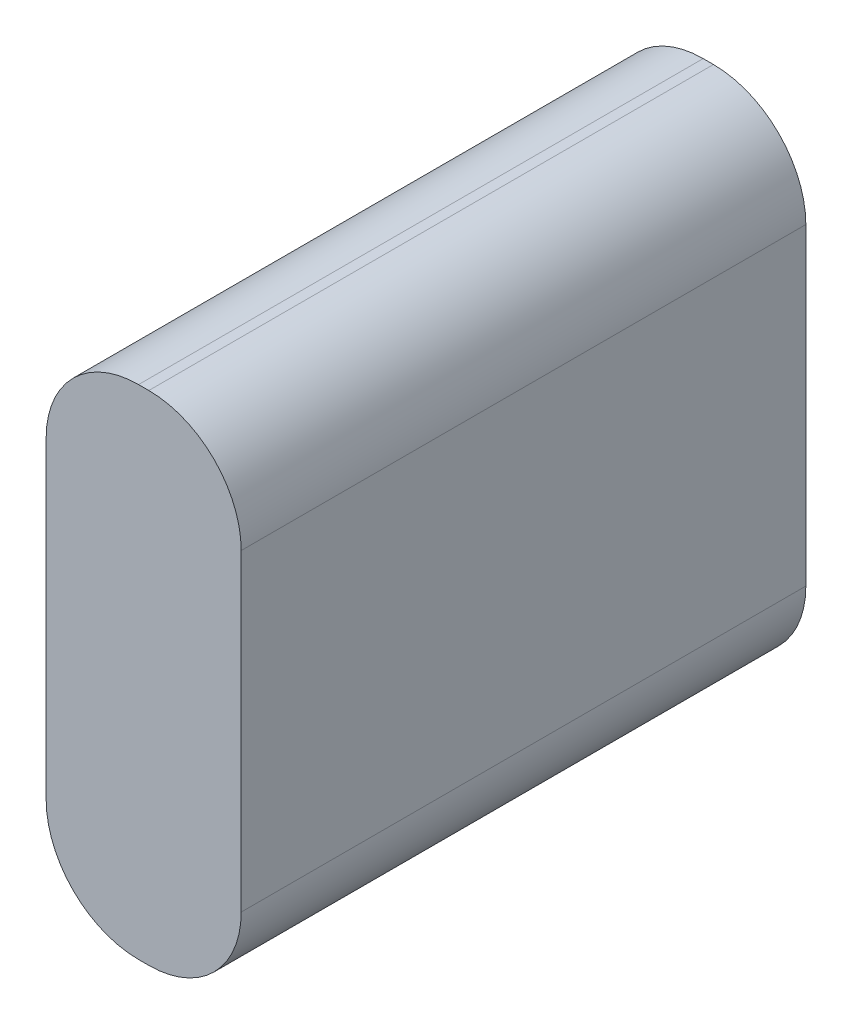
SolidWorks part; units mm, degrees
ref_plane "Front Plane" through (0, 0, 0) normal (0, 0, 1) x (1, 0, 0)
ref_plane "Top Plane" through (0, 0, 0) normal (0, 1, 0) x (1, 0, 0)
ref_plane "Right Plane" through (0, 0, 0) normal (1, 0, 0) x (0, 0, -1)
sketch "Sketch3" plane through (0, 0, 0) normal (0, 0, 1) x (1, 0, 0)
  line L1 (-25.6694, 45.72) -> (12.3306, 45.72)
  line L2 (-25.6694, 45.72) -> (-25.6694, -51.28)
  line L3 (-25.6694, -51.28) -> (12.3306, -51.28)
  line L4 (12.3306, 45.72) -> (12.3306, -51.28)
  dimension "D1" = 97
  dimension "D2" = 38
extrude "Boss-Extrude1" add sketch "Sketch3" along normal blind 110
fillet "Fillet2" radius 18 4 edges at (12.3306, -51.28, 55) (-25.6694, -51.28, 55) (-25.6694, 45.72, 55) (12.3306, 45.72, 55)
